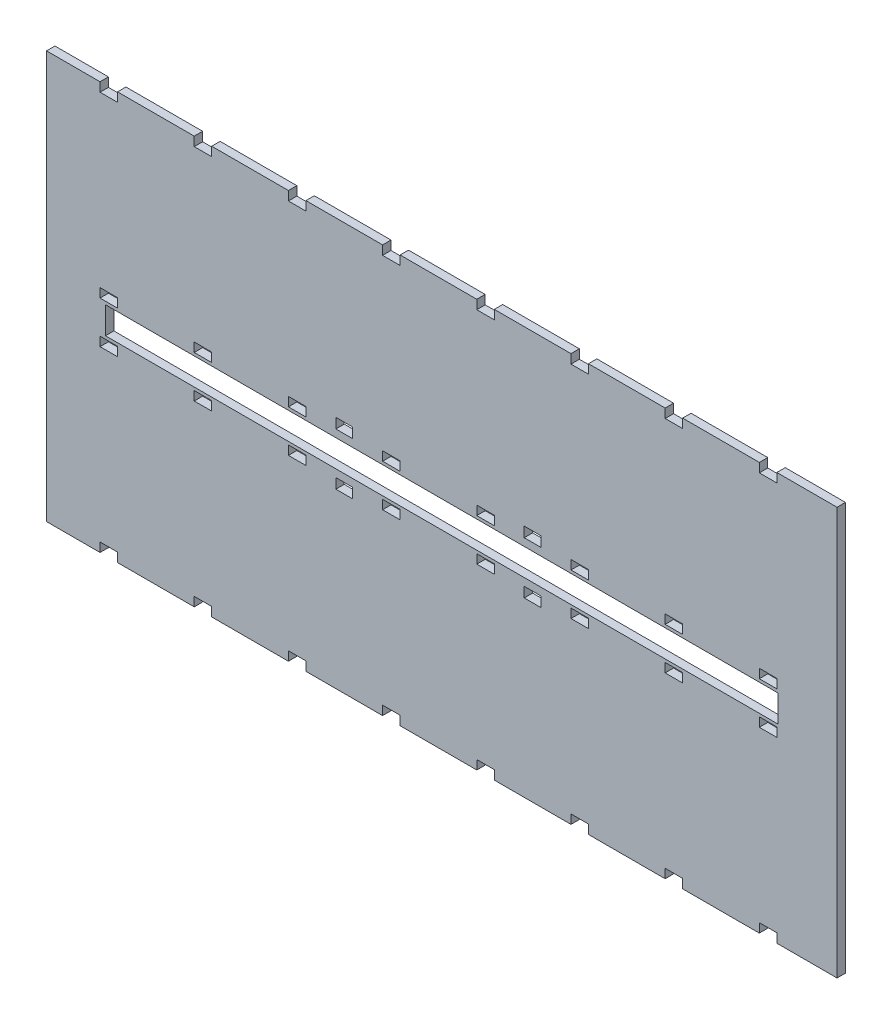
SolidWorks part; units mm, degrees
ref_plane "Front Plane" through (0, 0, 0) normal (0, 0, 1) x (1, 0, 0)
ref_plane "Top Plane" through (0, 0, 0) normal (0, 1, 0) x (1, 0, 0)
ref_plane "Right Plane" through (0, 0, 0) normal (1, 0, 0) x (0, 0, -1)
sketch "Sketch4" plane through (0, 0, 0) normal (0, 0, 1) x (1, 0, 0)
  line L0 (125.857, -5.08) -> (125.857, -19.05) construction
  line L1 (-150.368, 19.05) -> (148.082, 19.05)
  line L2 (125.857, -5.08) -> (-128.143, -5.08)
  line L3 (125.857, -5.08) -> (125.857, 5.08)
  line L4 (125.857, 5.08) -> (-128.143, 5.08)
  line L5 (-128.143, -5.08) -> (-128.143, 5.08)
  line L6 (-150.368, 19.05) -> (-150.368, -19.05)
  line L7 (-150.368, -19.05) -> (148.082, -19.05)
  line L8 (148.082, 19.05) -> (148.082, -19.05)
  line L9 (125.857, 5.08) -> (125.857, 19.05) construction
  line L10 (125.857, 5.08) -> (148.082, 5.08) construction
  line L11 (-128.143, 5.08) -> (-150.368, 5.08) construction
  dimension "D1" = 254
  dimension "D2" = 10.16
  dimension "D3" = 125.857
  dimension "D4" = 5.08
  dimension "D5" = 38.1
  dimension "D6" = 298.45
extrude "Boss-Extrude1" add sketch "Sketch4" along normal blind 3.175
sketch "Sketch5" plane through (0, 0, 3.175) normal (0, 0, 1) x (1, 0, 0)
  line L0 (148.082, 19.05) -> (-150.368, 19.05) construction
  line L1 (-130.175, 9.652) -> (-123.571, 9.652)
  line L2 (-130.175, 9.652) -> (-130.175, 6.223)
  line L3 (-130.175, 6.223) -> (-123.571, 6.223)
  line L4 (-123.571, 9.652) -> (-123.571, 6.223)
  line L9 (-150.368, 19.05) -> (-150.368, -19.05) construction
  point P4 (-126.873, 9.652)
  dimension "D1" = 9.398
  dimension "D2" = 23.495
  dimension "D3" = 6.604
  dimension "D4" = 3.429
extrude "Cut-Extrude1" cut sketch "Sketch5" against normal through all
sketch "Sketch7" plane through (0, 19.05, 0) normal (0, 1, 0) x (1, 0, 0)
  line L1 (148.082, 0) -> (-150.368, 0)
  line L2 (148.082, 0) -> (148.082, -3.175)
  line L3 (148.082, -3.175) -> (-150.368, -3.175)
  line L4 (-150.368, 0) -> (-150.368, -3.175)
extrude "Boss-Extrude2" add sketch "Sketch7" along normal blind 57.912
pattern_linear "LPattern3" count 2 spacing 67.31 along (0, 1, 0) count 8 spacing 35.56 along (1, 0, 0) of "Cut-Extrude1"
sketch "Sketch6" plane through (0, 0, 0) normal (0, 0, -1) x (-1, 0, 0)
  line L0 (23.495, 7.9375) -> (52.451, 7.9375) construction
  line L4 (37.973, 7.9375) -> (41.148, 7.9375)
  line L5 (41.148, 7.9375) -> (41.148, 11.7475)
  line L6 (41.148, 11.7475) -> (37.973, 11.7475)
  line L7 (37.973, 11.7475) -> (34.798, 11.7475)
  line L8 (34.798, 11.7475) -> (34.798, 7.9375)
  line L9 (34.798, 7.9375) -> (37.973, 7.9375)
  line L10 (23.495, 9.652) -> (23.495, 6.223) construction
  line L11 (52.451, 6.223) -> (52.451, 9.652) construction
  point P6 (24.5064, 8.2519)
  point P7 (23.495, 7.9375)
  point P14 (52.451, 7.9375)
  dimension "D1" = 3.81
  dimension "D2" = 6.35
extrude "Cut-Extrude2" cut sketch "Sketch6" against normal through all
pattern_linear "LPattern2" count 2 spacing 71.12 along (1, 0, 0) of "Cut-Extrude2"
mirror "Mirror1" about plane through (0, 0, 0) normal (0, 1, 0) of "LPattern3", "Boss-Extrude2", "LPattern2", "Cut-Extrude1", "Cut-Extrude2"
